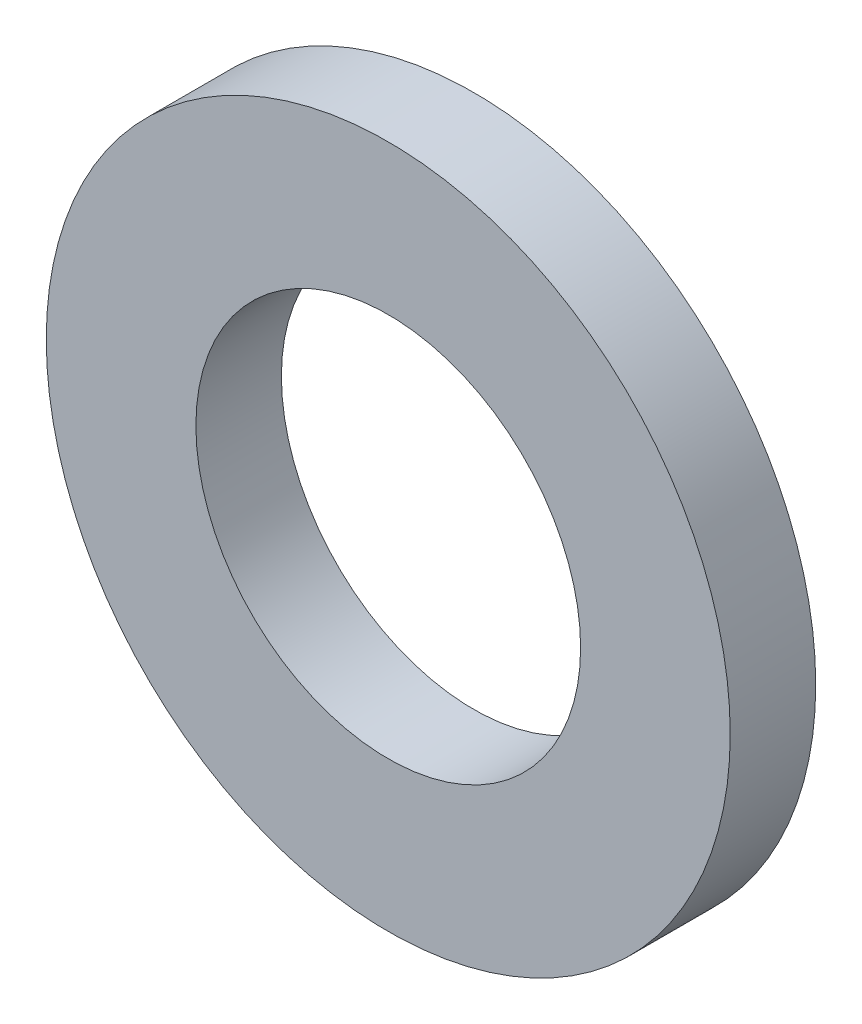
SolidWorks part; units mm, degrees
ref_plane "Front Plane" through (0, 0, 0) normal (0, 0, 1) x (1, 0, 0)
ref_plane "Top Plane" through (0, 0, 0) normal (0, 1, 0) x (1, 0, 0)
ref_plane "Right Plane" through (0, 0, 0) normal (1, 0, 0) x (0, 0, -1)
sketch "Sketch1" plane through (0, 0, 0) normal (0, 0, 1) x (1, 0, 0)
  circle A0 centre (0, 0) radius 8
  circle A1 centre (0, 0) radius 4.5
  dimension "D1" = 9
  dimension "D2" = 16
extrude "Boss-Extrude1" add sketch "Sketch1" along normal blind 2
